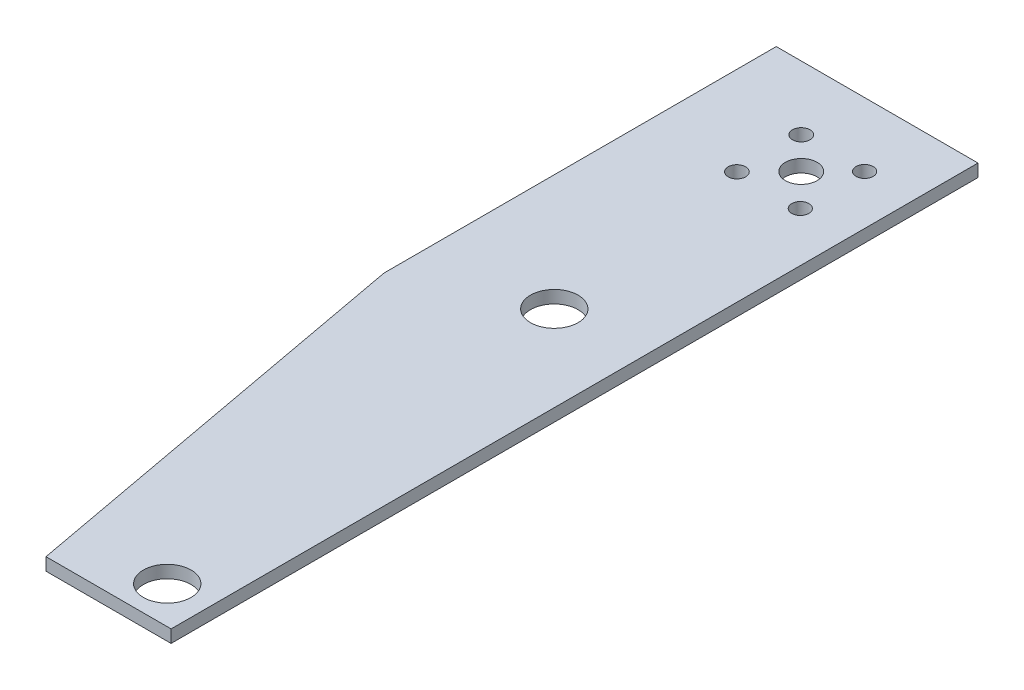
SolidWorks part; units mm, degrees
ref_plane "Front" through (0, 0, 0) normal (0, 0, 1) x (1, 0, 0)
ref_plane "Top" through (0, 0, 0) normal (0, 1, 0) x (1, 0, 0)
ref_plane "Right" through (0, 0, 0) normal (1, 0, 0) x (0, 0, -1)
sketch "Sketch1" plane through (0, 0, 0) normal (0, 1, 0) x (1, 0, 0)
  line L1 (0, 0) -> (50.8, 0)
  line L2 (0, 0) -> (0, 203.2)
  line L3 (0, 203.2) -> (50.8, 203.2)
  line L4 (50.8, 0) -> (50.8, 203.2)
  dimension "D1" = 50.8
  dimension "D2" = 203.2
extrude "Boss-Extrude1" add sketch "Sketch1" along normal blind 3.175
sketch "Sketch2" plane through (0, 3.175, 0) normal (0, 1, 0) x (1, 0, 0)
  circle A0 centre (22.3845, 187.1032) radius 2.2
  circle A1 centre (38.3645, 187.0823) radius 2.1596
  circle A2 centre (22.3634, 170.9285) radius 2.2
  circle A3 centre (38.3433, 170.9076) radius 2.1596
  circle A4 centre (30.3855, 179.1032) radius 4
  dimension "D1" = 8.001
  dimension "D2" = 8
extrude "Cut-Extrude1" cut sketch "Sketch2" against normal blind 10
sketch "Sketch5" plane through (0, 0, 0) normal (0, -1, 0) x (-1, 0, 0)
  circle A0 centre (-40.4628, 9.3689) radius 6
  circle A1 centre (-29.2592, 118.0365) radius 6
extrude "Cut-Extrude2" cut sketch "Sketch5" against normal blind 10
sketch "Sketch6" plane through (0, 3.175, 0) normal (0, 1, 0) x (1, 0, 0)
  line L0 (0, 0) -> (19.299, 0)
  line L1 (0, 0) -> (50.8, 0) construction
  line L2 (19.299, 0) -> (-0.185, 105.4315)
  line L3 (-0.185, 105.4315) -> (0, 0)
extrude "Cut-Extrude3" cut sketch "Sketch6" against normal blind 10
